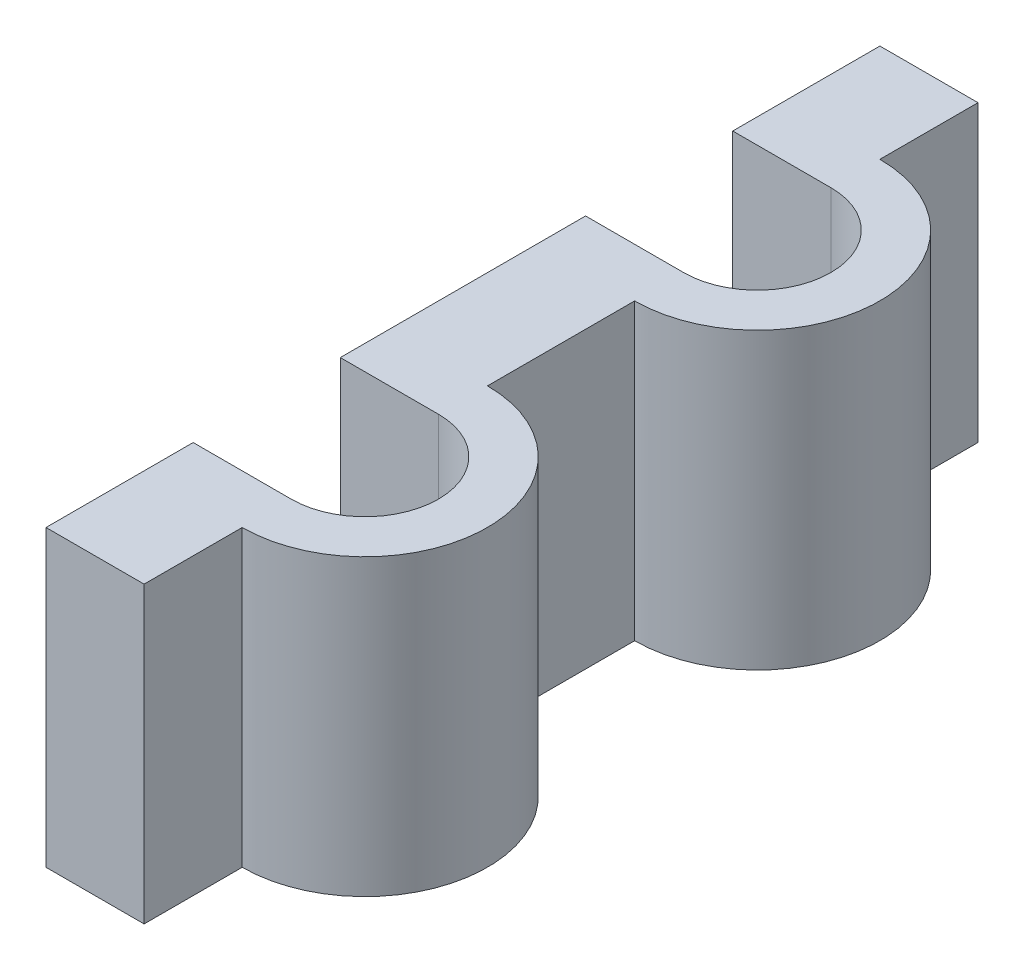
SolidWorks part; units mm, degrees
ref_plane "Front Plane" through (0, 0, 0) normal (0, 0, 1) x (1, 0, 0)
ref_plane "Top Plane" through (0, 0, 0) normal (0, 1, 0) x (1, 0, 0)
ref_plane "Right Plane" through (0, 0, 0) normal (1, 0, 0) x (0, 0, -1)
sketch "Sketch2" plane through (0, 0, 0) normal (0, 1, 0) x (1, 0, 0)
  line L0 (0, 0) -> (0, 15)
  line L1 (0, 0) -> (10, 0)
  line L2 (10, 0) -> (10, 10)
  line L3 (10, 35) -> (10, 50)
  line L4 (0, 42.5) -> (10, 42.5) construction
  line L7 (0, 15) -> (10, 15)
  line L8 (0, 30) -> (10, 30)
  line L9 (0, 30) -> (0, 55)
  line L10 (0, 55) -> (10, 55)
  line L11 (0, 70) -> (10, 70)
  line L12 (10, 85) -> (10, 75)
  line L13 (0, 85) -> (10, 85)
  line L14 (0, 85) -> (0, 70)
  arc A0 (10, 10) -> (10, 35) centre (10, 22.5) ccw
  arc A4 (10, 30) -> (10, 15) centre (10, 22.5) cw
  arc A5 (10, 55) -> (10, 70) centre (10, 62.5) ccw
  arc A6 (10, 75) -> (10, 50) centre (10, 62.5) cw
  point P12 (5, 15)
  dimension "D2" = 7.5
  dimension "D3" = 15
  dimension "D6" = 5
  dimension "D1" = 20
  dimension "D4" = 10
  dimension "D5" = 10
extrude "Boss-Extrude1" add sketch "Sketch2" along normal blind 30
